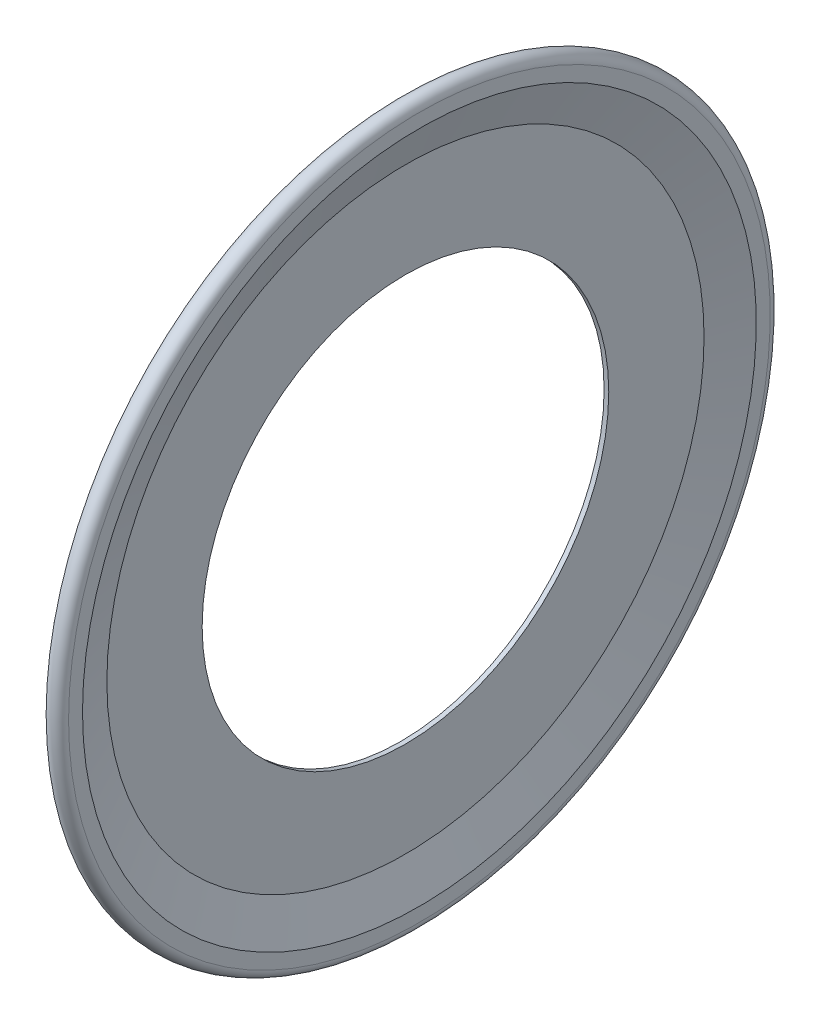
SolidWorks part; units mm, degrees
ref_plane "Front" through (0, 0, 0) normal (0, 0, 1) x (1, 0, 0)
ref_plane "Top" through (0, 0, 0) normal (0, 1, 0) x (1, 0, 0)
ref_plane "Right" through (0, 0, 0) normal (1, 0, 0) x (0, 0, -1)
sketch "Sketch1" plane through (0, 0, 0) normal (0, 0, 1) x (1, 0, 0)
  line L0 (-6, 0) -> (6, 0) construction
  line L1 (-5.8, 9) -> (-5.8, 8.75)
  line L2 (-5.8, 8.75) -> (-5.6, 8.75)
  line L3 (-5, 14.5) -> (-5, -14.5) construction
  line L4 (-5, 14.5) -> (-5, -14.5) construction
  line L5 (-5.6, 8.75) -> (-5.6, 9)
  line L9 (-5.6, 15.1) -> (-5.6, 14.5)
  line L15 (-5.2, 15.1) -> (-5.2, 14.5353)
  line L17 (-5, 14.5) -> (-5.6, 12.8515)
  line L18 (-5.2, 14.5353) -> (-5.8, 12.8868)
  line L19 (-5.8, 14.5) -> (-5.6, 14.5)
  line L20 (-5.8, 12.8868) -> (-5.8, 9)
  line L22 (-5.6, 12.8515) -> (-5.6, 9)
  line L23 (-5.8, 9) -> (-5.6, 9) construction
  line L25 (-5, 15.1) -> (-5, 14.5)
  line L27 (-5.8, 15.1) -> (-5.8, 14.5)
  arc A0 (-5.2, 15.1) -> (-5.6, 15.1) centre (-5.4, 15.1) ccw
  arc A1 (-5, 15.1) -> (-5.8, 15.1) centre (-5.4, 15.1) ccw
  dimension "D1" = 12
  dimension "D7" = 0.2
  dimension "D2" = 0.25
revolve "Revolve1" add sketch "Sketch1" angle 360 about L0
